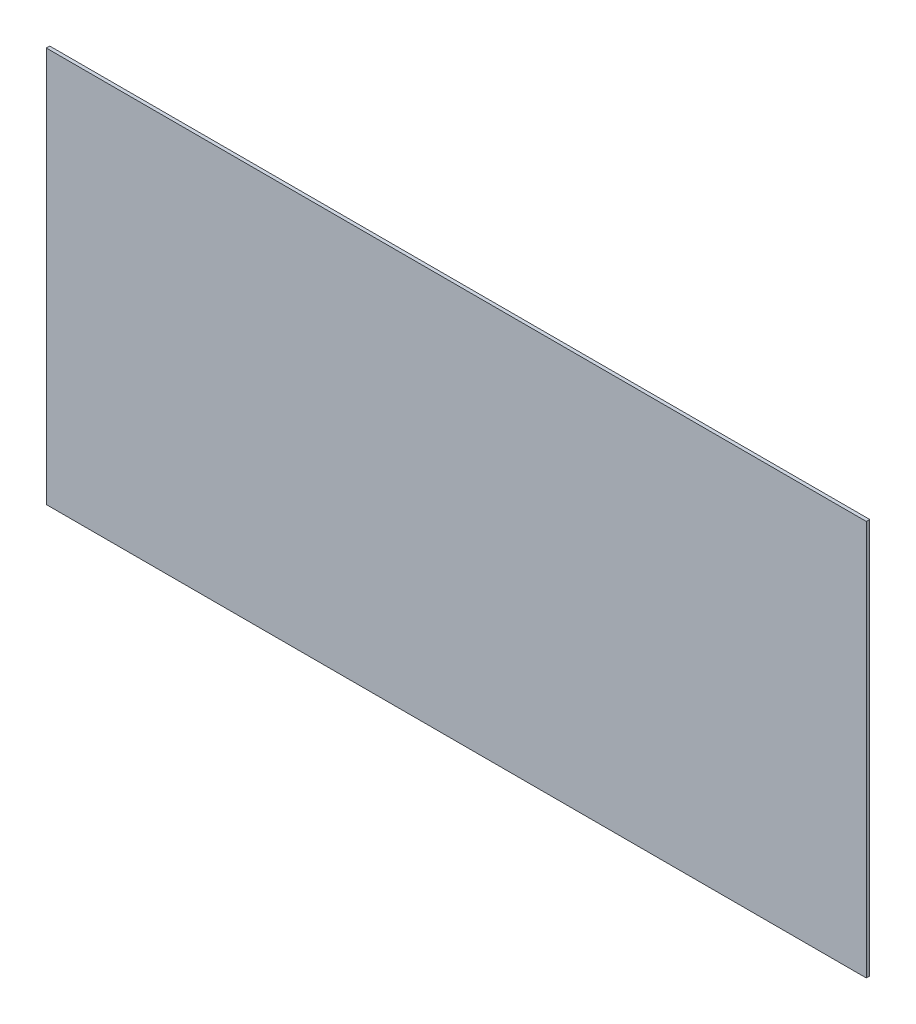
SolidWorks part; units mm, degrees
ref_plane "Front Plane" through (0, 0, 0) normal (0, 0, 1) x (1, 0, 0)
ref_plane "Top Plane" through (0, 0, 0) normal (0, 1, 0) x (1, 0, 0)
ref_plane "Right Plane" through (0, 0, 0) normal (1, 0, 0) x (0, 0, -1)
sketch "Sketch1" plane through (0, 0, 0) normal (0, 0, 1) x (1, 0, 0)
  line L1 (238.5, 115) -> (-238.5, 115)
  line L2 (238.5, 115) -> (238.5, -115)
  line L3 (238.5, -115) -> (-238.5, -115)
  line L4 (-238.5, 115) -> (-238.5, -115)
  line L5 (238.5, 115) -> (-238.5, -115) construction
  line L6 (238.5, -115) -> (-238.5, 115) construction
  point P0 (0, 0)
  dimension "D1" = 477
  dimension "D2" = 230
extrude "Boss-Extrude1" add sketch "Sketch1" along normal blind 2
